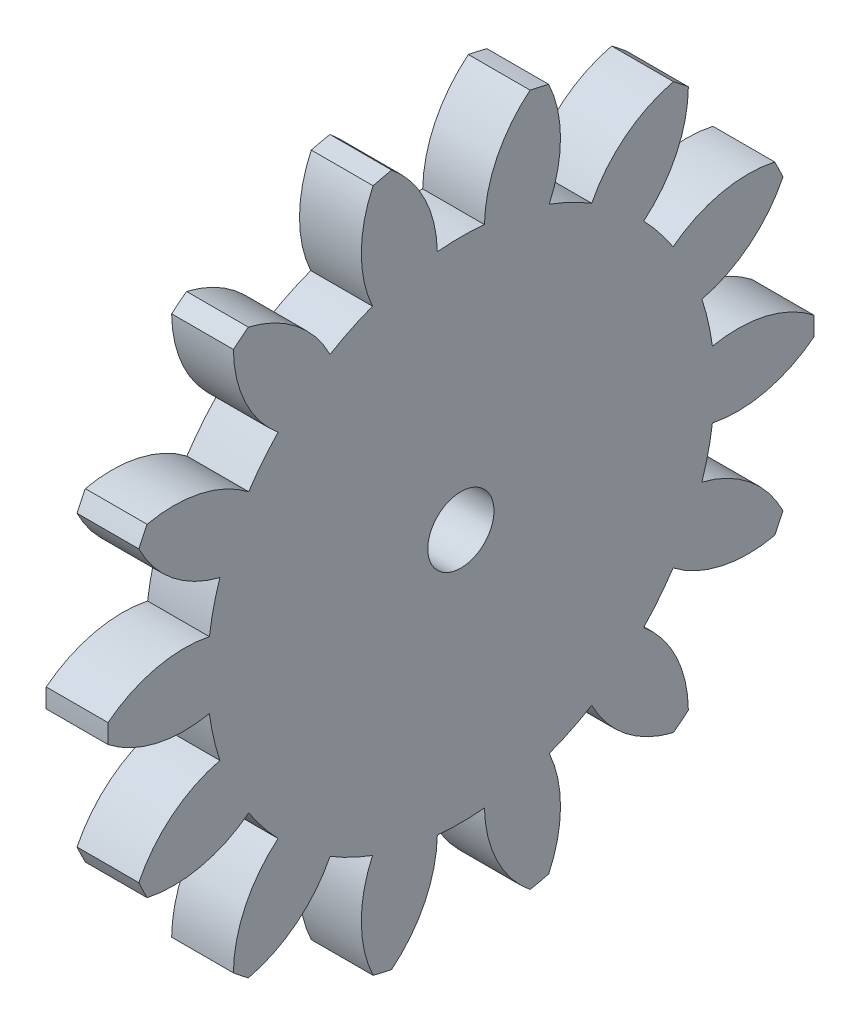
SolidWorks part; units mm, degrees
ref_plane "Plane1" through (0, 0, 0) normal (0, 0, 1) x (1, 0, 0)
ref_plane "Plane2" through (0, 0, 0) normal (0, 1, 0) x (1, 0, 0)
ref_plane "Plane3" through (0, 0, 0) normal (1, 0, 0) x (0, 0, -1)
sketch "HoldingSke" plane through (0, 0, 0) normal (0, 1, 0) x (1, 0, 0)
  line L0 (0, 0) -> (0.4851, -0.121)
  line L1 (-15, 0) -> (100, 0) construction
  line L2 (0, 0) -> (-2.1039, 2.3779)
  line L3 (0, 0) -> (-11.863, 4.5341)
  line L4 (0, 0) -> (8.3795, 2.0892)
  line L5 (0, 0) -> (-46.8476, -17.4728)
  line L6 (0, 0) -> (-2.3211, -1.5661)
  line L7 (-2.1039, 2.3779) -> (8.6586, 51.2059)
  line L8 (-76.2, 54.61) -> (-75.7, 54.61)
  line L9 (-71.009, 38.7566) -> (-53.1078, 45.2721)
  line L10 (-76.2, 71.12) -> (104.1128, 71.12)
  line L11 (0, 0) -> (-2.8, 0)
  line L12 (-76.2, 101.6) -> (-76.133, 101.6)
  line L13 (24.9733, 27.94) -> (52.9518, 28.4284)
  line L14 (24.9733, 27.94) -> (24.9743, 27.94)
  line L15 (24.9733, 27.94) -> (100.4006, 29.5858)
  line L16 (-63.627, -2) -> (-12.827, -2)
  circle A0 centre (0, 0) radius 1.5
  circle A1 centre (0, 0) radius 11.499
  circle A2 centre (0, 0) radius 37.5
  circle A3 centre (0, 0) radius 1.5
  dimension "MHD" = 22.998
  dimension "Hub_dia" = 75
  dimension "Bore" = 3
  dimension "MBD" = 3
  dimension "Num_teeth" = 14
  dimension "Pitch" = 0.5
  dimension "Overall_len" = 50
  dimension "Show_teeth" = 14
  dimension "Thickness" = 2.8
  dimension "OAL" = 50.0001
  dimension "T_dim" = 0.5
  dimension "Ap" = 20
  dimension "H" = 19.05
  dimension "Pitch_radius" = 180.3128
  dimension "Width" = 2.8
  dimension "Backlash" = 0.067
  dimension "Addendum_fac" = 1
  dimension "Dedendum_fac" = 1.25
  dimension "Clearance_fac" = 0.25
  dimension "Dedendum_add" = 0.001
  dimension "Module" = 2
sketch "BasProSke" plane through (0, 0, 0) normal (0, 1, 0) x (1, 0, 0)
  line L0 (-10, 0) -> (60, 0) construction
  line L1 (0, 0) -> (0, 16)
  line L2 (0, 0) -> (2.8, 0)
  line L3 (2.8, 0) -> (2.8, 16)
  line L4 (2.8, 16) -> (0, 16)
  dimension "Thickness" = 2.8
  dimension "Diameter" = 32
revolve "Base-Revolve" add sketch "BasProSke" angle 360 about L0
sketch "TooCutSke" plane through (0, 0, 0) normal (1, 0, 0) x (0, 0, -1)
  line L1 (0, 0) -> (0, 107) construction
  line L2 (0, 0) -> (-1.6846, 13.8983) construction
  line L3 (0, 0) -> (-6.1971, 27.1511) construction
  line L4 (-1.6846, 13.8983) -> (-3.0985, 13.5756) construction
  arc A0 (1.0679, 11.4493) -> (-1.0679, 11.4493) centre (0, 0) ccw
  arc A1 (3.1634, 15.7101) -> (-3.1634, 15.7101) centre (0, 0) ccw
  circle A2 centre (0, 0) radius 14 construction
  circle A3 centre (0, 0) radius 13.1557 construction
  arc A4 (-1.0679, 11.4493) -> (-3.1634, 15.7101) centre (-6.6668, 11.3413) ccw
  arc A5 (3.1634, 15.7101) -> (1.0679, 11.4493) centre (6.6668, 11.3413) ccw
  dimension "Root_dia" = 22.998
  dimension "Overcut_dia" = 32.0508
  dimension "Pitch_dia" = 28
  dimension "Base_dia" = 26.3114
  dimension "Flank_rad" = 5.6
  dimension "Half_ang" = 12.857
  dimension "Half_CT" = 1.4503
extrude "ToothCut" cut sketch "TooCutSke" along normal through all
fillet "Breaks" [suppressed] radius 0.04
fillet "RootFillets" [suppressed] radius 0.501
pattern_circular "TeethCuts" count 14 every 25.714 about axis through (-10, 0, 0) along (1, 0, 0) of "ToothCut", "RootFillets", "Breaks"
sketch "HubNeaOneSke" plane through (0, 0, 0) normal (-1, 0, 0) x (0, 0, 1)
  circle A0 centre (0, 0) radius 11.499
  dimension "Diameter" = 22.998
extrude "HubNearOne" [suppressed] add sketch "HubNeaOneSke" along normal blind 47.2001
sketch "HubNeaBotSke" plane through (0, 0, 0) normal (-1, 0, 0) x (0, 0, 1)
  circle A0 centre (0, 0) radius 11.499
  dimension "Diameter" = 22.998
extrude "HubNearBoth" [suppressed] add sketch "HubNeaBotSke" along normal blind 23.6
ref_plane "FarPln" through (2.8, 0, 0) normal (1, 0, 0) x (0, 0, -1)
sketch "HubFarSke" plane through (2.8, 0, 0) normal (1, 0, 0) x (0, 0, -1)
  circle A0 centre (0, 0) radius 11.499
  dimension "Diameter" = 22.998
extrude "HubFar" [suppressed] add sketch "HubFarSke" along normal blind 23.6
sketch "BorSke" plane through (0, 0, 0) normal (1, 0, 0) x (0, 0, -1)
  circle A0 centre (0, 0) radius 1.5
  dimension "Diameter" = 3
extrude "Bore" cut sketch "BorSke" along normal mid plane 100.0001
sketch "KeySke" plane through (0, 0, 0) normal (1, 0, 0) x (0, 0, -1)
  line L0 (-0.6, 0) -> (-0.6, 2)
  line L1 (-0.6, 2) -> (0.6, 2)
  line L2 (0.6, 2) -> (0.6, 0)
  line L3 (0, 0) -> (0, 34) construction
  line L4 (-0.6, 0) -> (0.6, 0)
  dimension "Offset" = 2
  dimension "Width" = 1.2
extrude "Keyway" [suppressed] cut sketch "KeySke" along normal mid plane 100.0001
pattern_circular "Keyway2" [suppressed] count 2 every 90 about axis through (-10, 0, 0) along (1, 0, 0)
equation "' \"Module@HoldingSke\" = 6.35"
equation "' \"Num_teeth@HoldingSke\" = 12"
equation "' \"Ap@HoldingSke\" =  20"
equation "' \"Ap@HoldingSke\" = 20"
equation "' \"Width@HoldingSke\" = 0.5 * 25.4"
equation "' \"Hub_dia@HoldingSke\"= 1 * 25.4"
equation "' \"Hub_dia@HoldingSke\" = 1 * 25.4"
equation "' \"Overall_len@HoldingSke\" = 1.0 * 25.4"
equation "' \"Bore@HoldingSke\" = 0.75 * 25.4"
equation "' \"T_dim@HoldingSke\" = 0.1 * 25.4"
equation "' \"Width@KeySke\" = 0.25 * 25.4"
equation "' \"Show_teeth@HoldingSke\" = 13"
equation "' \"Backlash@HoldingSke\" = 0.009 * 25.4"
equation "' \"Addendum_fac@HoldingSke\" = 1.0"
equation "' \"Dedendum_fac@HoldingSke\" = 1.25"
equation "' \"Dedendum_add@HoldingSke\" = 0.00005 * 25.4"
equation "' \"Clearance_fac@HoldingSke\" = 0.25"
equation "\"Pitch@HoldingSke\" = 1 / \"Module@HoldingSke\""
equation "\"Overcut_dia@TooCutSke\" = (\"Num_teeth@HoldingSke\" + 2 * \"Addendum_fac@HoldingSke\") / \"Pitch@HoldingSke\" + 0.002 * 25.4"
equation "\"Pitch_dia@TooCutSke\" = \"Num_teeth@HoldingSke\" / \"Pitch@HoldingSke\""
equation "\"Base_dia@TooCutSke\" = \"Num_teeth@HoldingSke\" / \"Pitch@HoldingSke\" * cos((\"Ap@HoldingSke\"  * 3.14159265 / 180))"
equation "\"Root_dia@TooCutSke\" = (\"Num_teeth@HoldingSke\" + 2) / \"Pitch@HoldingSke\" - 2 * (\"Addendum_fac@HoldingSke\" + \"Dedendum_fac@HoldingSke\") / \"Pitch@HoldingSke\" - \"Dedendum_add@HoldingSke\" * 2"
equation "\"Half_ang@TooCutSke\" = 180 / \"Num_teeth@HoldingSke\""
equation "\"Half_CT@TooCutSke\" = \"Num_teeth@HoldingSke\" / \"Pitch@HoldingSke\" * sin((3.14159265 / 2 / \"Num_teeth@HoldingSke\")) / 2 - 7 * \"Backlash@HoldingSke\" / 4"
equation "\"Flank_rad@TooCutSke\" = \"Num_teeth@HoldingSke\" / \"Pitch@HoldingSke\" / 5"
equation "\"Radius@RootFillets\" = \"Clearance_fac@HoldingSke\" / \"Pitch@HoldingSke\" + \"Dedendum_add@HoldingSke\""
equation "\"Break_rad@Breaks\" = 0.02 / \"Pitch@HoldingSke\""
equation "\"Thickness@HoldingSke\" = \"Width@HoldingSke\""
equation "\"OAL@HoldingSke\" = \"Thickness@HoldingSke\""
equation "\"MHD@HoldingSke\" = (\"Num_teeth@HoldingSke\" + 2) / \"Pitch@HoldingSke\" - 2 * (\"Addendum_fac@HoldingSke\" + \"Dedendum_fac@HoldingSke\")  / \"Pitch@HoldingSke\" - \"Dedendum_add@HoldingSke\" * 2"
equation "\"MBD@HoldingSke\" = (\"Num_teeth@HoldingSke\" + 2) / \"Pitch@HoldingSke\" - 2 * (\"Addendum_fac@HoldingSke\" + \"Dedendum_fac@HoldingSke\")  / \"Pitch@HoldingSke\" - \"Dedendum_add@HoldingSke\" * 2 - 0.002 * 25.4"
equation "\"MHD@HoldingSke\" = ((sgn( \"MHD@HoldingSke\" - \"Hub_dia@HoldingSke\" )-1)*( \"MHD@HoldingSke\" - \"Hub_dia@HoldingSke\" ))/-2+ \"Hub_dia@HoldingSke\""
equation "\"MBD@HoldingSke\" = ((sgn( \"MBD@HoldingSke\" - \"Bore@HoldingSke\" )-1)*( \"MBD@HoldingSke\" - \"Bore@HoldingSke\" ))/-2+ \"Bore@HoldingSke\""
equation "\"OAL@HoldingSke\" = ((sgn( \"OAL@HoldingSke\" - \"Overall_len@HoldingSke\" )+1)*( \"OAL@HoldingSke\" - \"Overall_len@HoldingSke\" ))/2 + \"Overall_len@HoldingSke\" + 0.000002 * 25.4"
equation "\"Num_teeth@TeethCuts\" = int( \"Show_teeth@HoldingSke\" ) + 1"
equation "\"Num_teeth@TeethCuts\" = ((sgn( \"Num_teeth@TeethCuts\" - \"Num_teeth@HoldingSke\" )-1)*( \"Num_teeth@TeethCuts\" - \"Num_teeth@HoldingSke\" ))/-2+ \"Num_teeth@HoldingSke\""
equation "\"Num_teeth@TeethCuts\" = ((sgn( \"Num_teeth@TeethCuts\" - 2.0)+1)*( \"Num_teeth@TeethCuts\" - 2.0))/2 +2.0"
equation "\"Angle@TeethCuts\" = 360.0 / \"Num_teeth@HoldingSke\""
equation "\"Diameter@BasProSke\" = (\"Num_teeth@HoldingSke\" + 2 * \"Addendum_fac@HoldingSke\") / \"Pitch@HoldingSke\""
equation "\"Thickness@BasProSke\"  = \"Thickness@HoldingSke\""
equation "' \"Fillet_rad@BasProSke\" =  \"Thickness@HoldingSke\" * 0.05"
equation "' \"Fillet_rad@BasProSke\" = \"Thickness@HoldingSke\" * 0.05"
equation "\"MHD@HoldingSke\" = ((sgn( \"MHD@HoldingSke\" - \"Root_dia@TooCutSke\" )-1)*( \"MHD@HoldingSke\" - \"Root_dia@TooCutSke\" ))/-2+ \"Root_dia@TooCutSke\""
equation "\"Diameter@HubNeaOneSke\" = \"MHD@HoldingSke\""
equation "\"Length@HubNearOne\" = \"OAL@HoldingSke\" - \"Thickness@BasProSke\""
equation "\"Diameter@HubNeaBotSke\" = \"MHD@HoldingSke\""
equation "\"Length@HubNearBoth\" = ( \"OAL@HoldingSke\" - \"Thickness@BasProSke\" ) / 2.0"
equation "\"Thickness@FarPln\" = \"Thickness@BasProSke\""
equation "\"Diameter@HubFarSke\" = \"MHD@HoldingSke\""
equation "\"Length@HubFar\" = ( \"OAL@HoldingSke\" - \"Thickness@BasProSke\" ) / 2.0"
equation "\"Diameter@BorSke\" = \"MBD@HoldingSke\""
equation "\"D1@Bore\" = \"OAL@HoldingSke\" * 2.0"
equation "\"D1@Keyway\" = \"OAL@HoldingSke\" * 2.0"
equation "\"Offset@KeySke\" = \"T_dim@HoldingSke\" + \"MBD@HoldingSke\" / 2.0"
